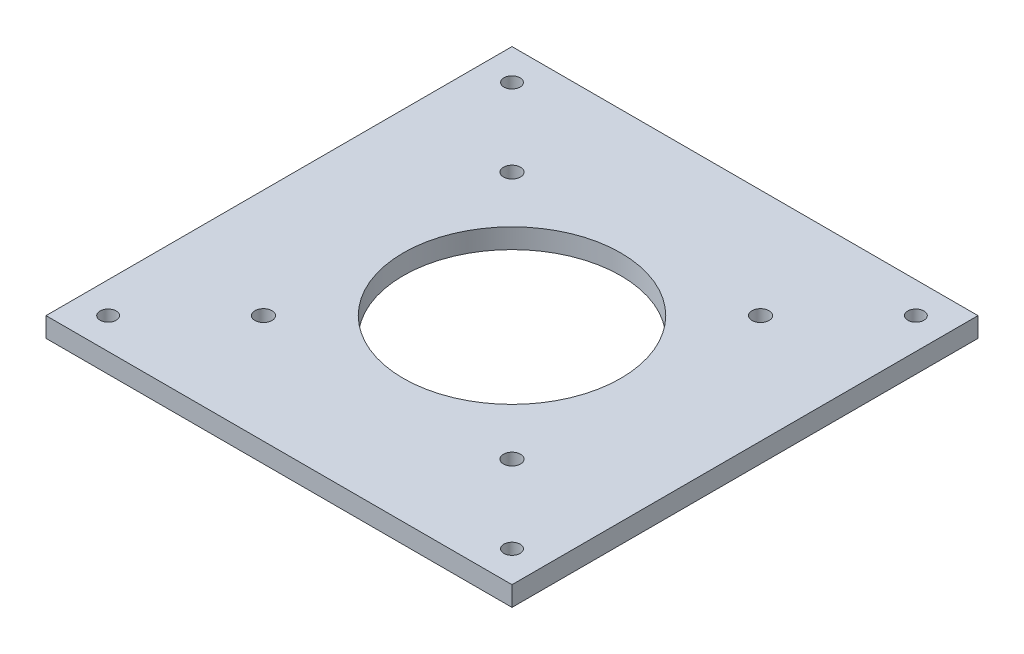
SolidWorks part; units mm, degrees
ref_plane "Front Plane" through (0, 0, 0) normal (0, 0, 1) x (1, 0, 0)
ref_plane "Top Plane" through (0, 0, 0) normal (0, 1, 0) x (1, 0, 0)
ref_plane "Right Plane" through (0, 0, 0) normal (1, 0, 0) x (0, 0, -1)
sketch "Sketch2" plane through (0, 0, 0) normal (0, 1, 0) x (1, 0, 0)
  line L0 (0, 61.8644) -> (0, -41.9492) construction
  line L1 (45.7627, 0) -> (-92.7966, 0) construction
  line L3 (75, -75) -> (-75, -75)
  line L4 (75, -75) -> (75, 75)
  line L5 (75, 75) -> (-75, 75)
  line L6 (-75, -75) -> (-75, 75)
  line L7 (75, -75) -> (-75, 75) construction
  line L8 (75, 75) -> (-75, -75) construction
  circle A0 centre (-65, 65) radius 2.6
  circle A1 centre (65, 65) radius 2.6
  circle A2 centre (65, -65) radius 2.6
  circle A3 centre (-65, -65) radius 2.6
  circle A4 centre (-40, 40) radius 2.75
  circle A5 centre (40, 40) radius 2.75
  circle A6 centre (40, -40) radius 2.75
  circle A7 centre (-40, -40) radius 2.75
  circle A8 centre (0, 0) radius 35
  point P1 (0, 0)
  dimension "D3" = 65
  dimension "D4" = 40
  dimension "D5" = 5.5
  dimension "D6" = 70
  dimension "D1" = 150
  dimension "D2" = 150
extrude "Boss-Extrude1" add sketch "Sketch2" along normal blind 6.35
equation "\"connector_D1\" = 70 'the big holes diameter"
equation "\"mtg_hole_D\" = 5.5 'mounting holes"
equation "\"mtg_dfc\" = 40 'mounting hole distance from center"
equation "\"plate_thickness\" = 6.35 'thickness of the plate "
equation "\"t_height\" = 200"
equation "\"t_width\" = 240"
equation "\"t_length\" = 240"
equation "\"plate_hole_from_edge\" = 9"
equation "\"plate_spacing\" = 1"
equation "\"front_plate_height\" = \"t_height\" + 38"
equation "\"front_plate_width\" = \"t_width\" + 38"
equation "\"side_plate_height\" = \"front_plate_height\""
equation "\"side_plate_length\" = \"t_length\" + 38"
equation "\"top_plate_width\" = \"front_plate_width\""
equation "\"top_plate_length\" = \"side_plate_length\""
equation "\"itx_support_t_slot_length\" = \"t_width\" + (2 * 20.5)"
equation "\"locomotion_length\" = \"t_length\""
equation "\"locomotion_width\" = \"t_width\""
equation "\"locomotion_height\" = 40"
equation "\"itx_mtg_hole_spacing\" = 40"
equation "\"emg30_bracket_hole_len\" = 60"
equation "\"emg30_bracket_hole_wid\" = 11"
equation "\"perce_t_height\" = 50"
equation "\"perce_top_width\" = 150"
equation "\"perce_mtg_hole_spacing\" = \"perce_top_width\" - 20"
equation "\"D1@Sketch2\"=\"perce_top_width\""
equation "\"D2@Sketch2\"=\"perce_top_width\""
equation "\"D1@Boss-Extrude1\"=\"plate_thickness\""
equation "\"D3@Sketch2\"=\"perce_mtg_hole_spacing\"/2"
equation "\"D5@Sketch2\"=\"mtg_hole_D\""
equation "\"D4@Sketch2\"=\"mtg_dfc\""
equation "\"D6@Sketch2\"=\"connector_D1\""
